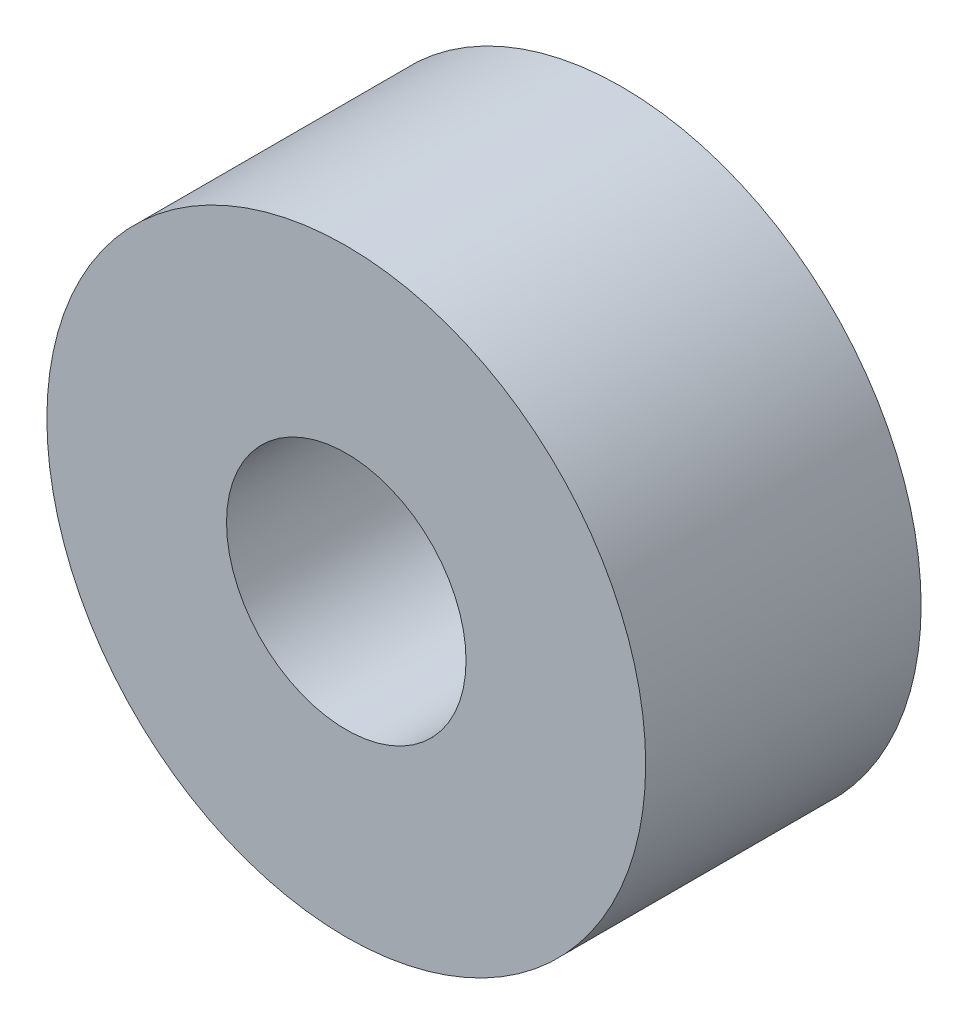
SolidWorks part; units mm, degrees
ref_plane "前视基准面" through (0, 0, 0) normal (0, 0, 1) x (1, 0, 0)
ref_plane "上视基准面" through (0, 0, 0) normal (0, 1, 0) x (1, 0, 0)
ref_plane "右视基准面" through (0, 0, 0) normal (1, 0, 0) x (0, 0, -1)
sketch "草图1" plane through (0, 0, 0) normal (0, 0, 1) x (1, 0, 0)
  circle A0 centre (0, 0) radius 2.5
  circle A1 centre (0, 0) radius 1
  dimension "D1" = 5
  dimension "D2" = 2
extrude "凸台-拉伸1" add sketch "草图1" along normal blind 2.3
